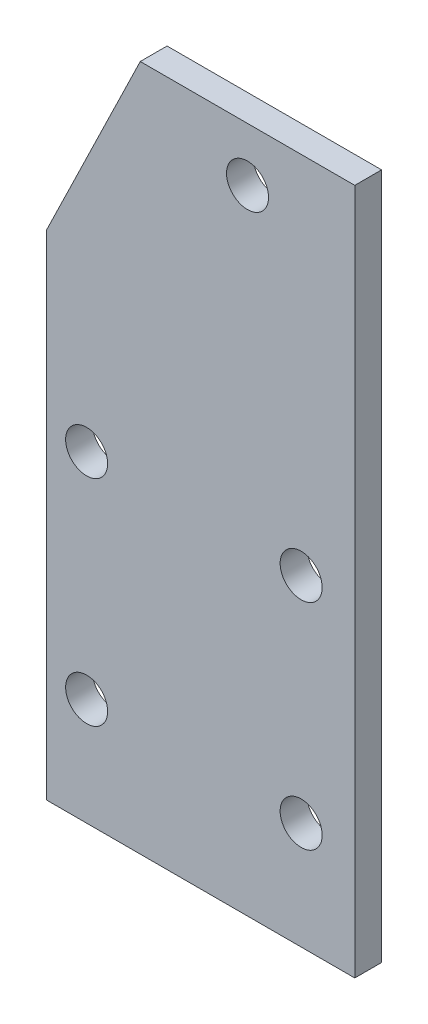
SolidWorks part; units mm, degrees
material "6061-T6 (SS)"
ref_plane "Front Plane" through (0, 0, 0) normal (0, 0, 1) x (1, 0, 0)
ref_plane "Top Plane" through (0, 0, 0) normal (0, 1, 0) x (1, 0, 0)
ref_plane "Right Plane" through (0, 0, 0) normal (1, 0, 0) x (0, 0, -1)
sketch "Sketch1" plane through (0, 0, 0) normal (0, 0, 1) x (1, 0, 0)
  line L0 (-12.7, 12.7) -> (12.7, -12.7) construction
  line L5 (12.7, 12.7) -> (-12.7, -12.7) construction
  line L6 (19.05, 33.02) -> (19.05, 55.88)
  line L12 (-17.4625, 33.02) -> (-17.4625, -25.4)
  line L13 (-17.4625, -25.4) -> (19.05, -25.4)
  line L14 (19.05, 33.02) -> (19.05, -25.4)
  line L15 (19.05, 55.88) -> (-6.35, 55.88)
  line L16 (-6.35, 55.88) -> (-17.4625, 33.02)
  circle A0 centre (-12.7, 12.7) radius 2.4892
  circle A1 centre (-12.7, -12.7) radius 2.4892
  circle A2 centre (12.7, 12.7) radius 2.4892
  circle A3 centre (12.7, -12.7) radius 2.4892
  circle A5 centre (6.35, 49.53) radius 2.4892
  point P0 (0, 0)
  point P2 (0, 0)
  point P3 (0, 0)
  point P20 (6.2535, 49.511)
  point P22 (0, 0)
  point P23 (3.81, 55.88)
  dimension "D1" = 4.9784
  dimension "D3" = 25.4
  dimension "D6" = 12.7
  dimension "D5" = 4.7625
  dimension "D10" = 12.7
  dimension "D12" = 4.9784
  dimension "D2" = 25.4
  dimension "D4" = 58.42
  dimension "D7" = 36.5125
  dimension "D8" = 22.86
  dimension "D9" = 25.4
  dimension "D11" = 6.35
extrude "Boss-Extrude1" add sketch "Sketch1" along normal blind 3.175
